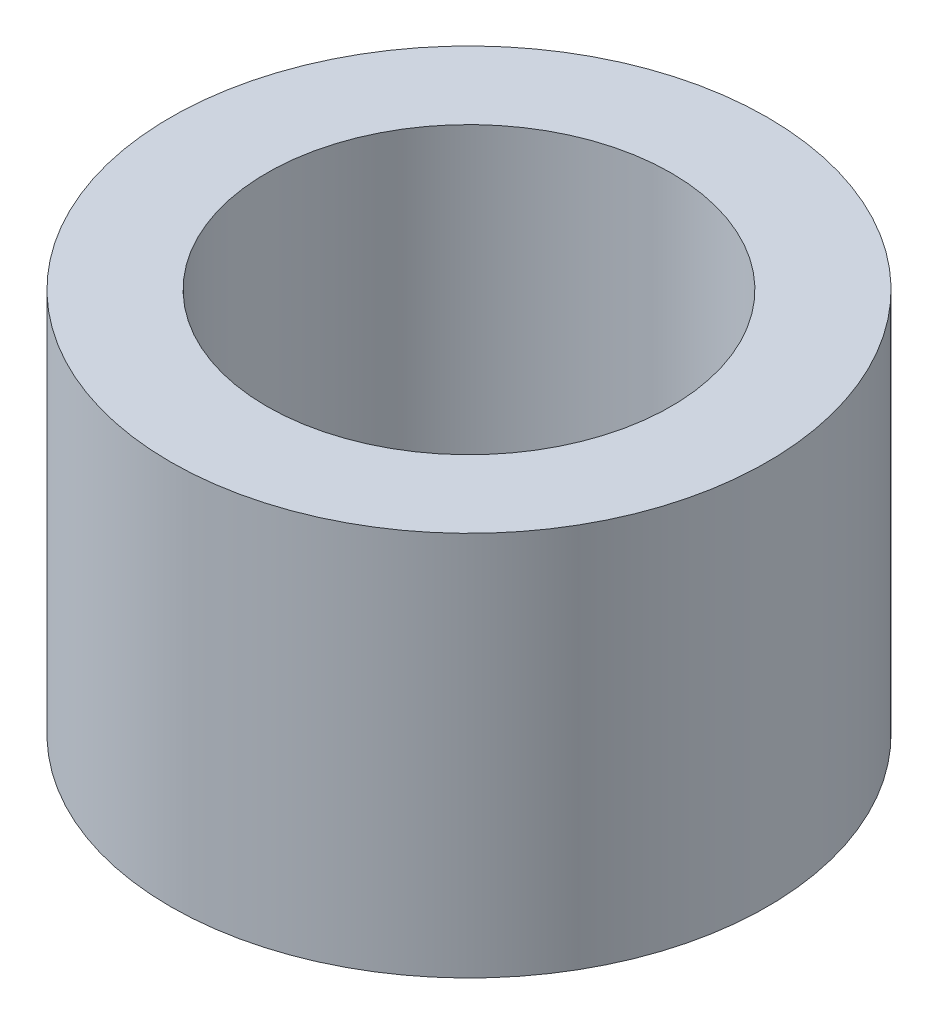
SolidWorks part; units mm, degrees
material "ABS"
ref_plane "Front Plane" through (0, 0, 0) normal (0, 0, 1) x (1, 0, 0)
ref_plane "Top Plane" through (0, 0, 0) normal (0, 1, 0) x (1, 0, 0)
ref_plane "Right Plane" through (0, 0, 0) normal (1, 0, 0) x (0, 0, -1)
sketch "Sketch1" plane through (0, 0, 0) normal (0, 1, 0) x (1, 0, 0)
  circle A0 centre (0, 0) radius 2.667
  circle A1 centre (0, 0) radius 3.937
  dimension "D1" = 5.334
  dimension "D2" = 1.27
extrude "Boss-Extrude1" add sketch "Sketch1" along normal blind 5.08
